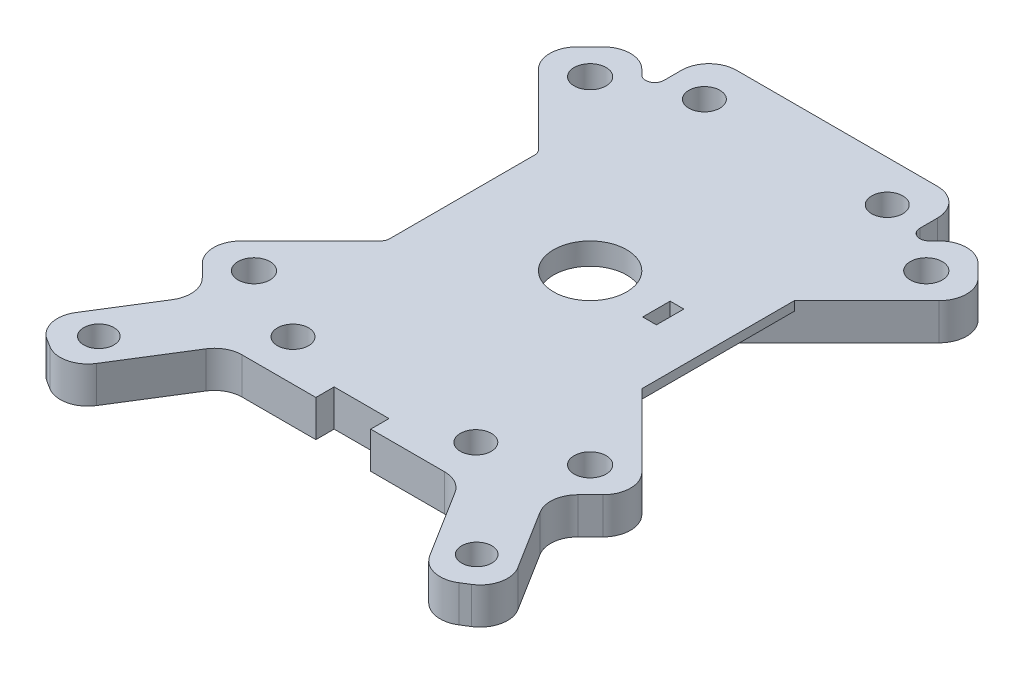
SolidWorks part; units mm, degrees
ref_plane "Front Plane" through (0, 0, 0) normal (0, 0, 1) x (1, 0, 0)
ref_plane "Top Plane" through (0, 0, 0) normal (0, 1, 0) x (1, 0, 0)
ref_plane "Right Plane" through (0, 0, 0) normal (1, 0, 0) x (0, 0, -1)
sketch "Sketch1" plane through (0, 0, 0) normal (0, 1, 0) x (1, 0, 0)
  line L1 (-14, -27) -> (14, -27)
  line L2 (-14, -27) -> (-14, 27)
  line L3 (-14, 27) -> (14, 27)
  line L4 (14, -27) -> (14, 27)
  line L5 (-14, -27) -> (14, 27) construction
  line L6 (-14, 27) -> (14, -27) construction
  point P0 (0, 0)
  dimension "D1" = 54
  dimension "D2" = 28
extrude "Boss-Extrude1" add sketch "Sketch1" along normal blind 4
sketch "Sketch10" plane through (0, 0, 0) normal (0, 1, 0) x (1, 0, 0)
  line L0 (-2.9682, -1.8547) -> (2.9682, 1.8547)
  line L1 (-2.9682, -1.8547) -> (19.8184, -38.3208)
  line L2 (2.9682, 1.8547) -> (25.7547, -34.6114)
  line L3 (19.8184, -38.3208) -> (25.7547, -34.6114)
  line L4 (0, -2.2) -> (0, 2.2) construction
  line L5 (-2.9682, 1.8547) -> (-25.7547, -34.6114)
  line L6 (-19.8184, -38.3208) -> (-25.7547, -34.6114)
  line L7 (2.9682, -1.8547) -> (-19.8184, -38.3208)
  line L8 (2.9682, -1.8547) -> (-2.9682, 1.8547)
  point P0 (0, 0)
  dimension "D1" = 32
  dimension "D2" = 43
  dimension "D3" = 7
extrude "Boss-Extrude4" add sketch "Sketch10" along normal blind 4 contours L8 L7 L1 L3 L2 L0 | L0 L8 L5 L6 L7 L1
sketch "Sketch2" plane through (0, 0, 0) normal (0, 1, 0) x (1, 0, 0)
  line L0 (2.8284, -2.8284) -> (24.0416, 18.3848)
  line L1 (2.8284, -2.8284) -> (-2.8284, 2.8284)
  line L2 (24.0416, 18.3848) -> (18.3848, 24.0416)
  line L3 (-2.8284, 2.8284) -> (18.3848, 24.0416)
  line L4 (14, 27) -> (-14, 27) construction
  line L10 (-2.8284, 2.8284) -> (2.8284, -2.8284)
  line L17 (-2.8284, -2.8284) -> (18.3848, -24.0416)
  line L18 (-2.8284, -2.8284) -> (2.8284, 2.8284)
  line L19 (2.8284, 2.8284) -> (24.0416, -18.3848)
  line L20 (18.3848, -24.0416) -> (24.0416, -18.3848)
  line L21 (-2.8284, 2.8284) -> (-24.0416, -18.3848)
  line L22 (-2.8284, 2.8284) -> (2.8284, -2.8284)
  line L23 (2.8284, -2.8284) -> (-18.3848, -24.0416)
  line L24 (-24.0416, -18.3848) -> (-18.3848, -24.0416)
  line L25 (2.8284, 2.8284) -> (-18.3848, 24.0416)
  line L26 (2.8284, 2.8284) -> (-2.8284, -2.8284)
  line L27 (-2.8284, -2.8284) -> (-24.0416, 18.3848)
  line L28 (-18.3848, 24.0416) -> (-24.0416, 18.3848)
  circle A1 centre (18.3848, 18.3848) radius 1.75
  circle A2 centre (18.3848, -18.3848) radius 1.75
  circle A3 centre (-18.3848, -18.3848) radius 1.75
  circle A4 centre (-18.3848, 18.3848) radius 1.75
  point P6 (0, 0)
  point P8 (0, 0)
  point P11 (0, 0)
  dimension "D4" = 3.5
  dimension "D1" = 135
  dimension "D2" = 8
  dimension "D3" = 30
  dimension "D5" = 4
extrude "Boss-Extrude2" add sketch "Sketch2" along normal blind 4
sketch "Sketch3" plane through (0, 4, 0) normal (0, 1, 0) x (1, 0, 0)
  circle A0 centre (10, -22.5) radius 1.7
  circle A1 centre (-10, -22.5) radius 1.7
  circle A2 centre (-10, 22.5) radius 1.7
  circle A3 centre (10, 22.5) radius 1.7
  dimension "D3" = 3.4
  dimension "D1" = 22.5
  dimension "D2" = 10
  dimension "D6" = 10
  dimension "D7" = 22.5
  dimension "D4" = 2
  dimension "D5" = 2
extrude "Cut-Extrude1" cut sketch "Sketch3" against normal blind 4
sketch "Sketch4" plane through (0, 4, 0) normal (0, 1, 0) x (1, 0, 0)
  line L1 (7.25, -1.5) -> (8.75, -1.5)
  line L2 (7.25, -1.5) -> (7.25, 1.5)
  line L3 (7.25, 1.5) -> (8.75, 1.5)
  line L4 (8.75, -1.5) -> (8.75, 1.5)
  line L5 (7.25, -1.5) -> (8.75, 1.5) construction
  line L6 (7.25, 1.5) -> (8.75, -1.5) construction
  circle A0 centre (0, 0) radius 4
  point P3 (8, 0)
  point P8 (8, 1.5)
  dimension "D1" = 8
  dimension "D2" = 8
  dimension "D3" = 1.5
  dimension "D4" = 3
extrude "Cut-Extrude2" cut sketch "Sketch4" against normal up to next
sketch "Sketch5" plane through (0, 0, 0) normal (0, -1, 0) x (1, 0, 0)
  line L0 (6.7082, -6) -> (-6.7082, -6)
  line L1 (6.7082, 6) -> (-6.7082, 6)
  arc A0 (6.7082, -6) -> (6.7082, 6) centre (0, 0) ccw
  arc A1 (-6.7082, 6) -> (-6.7082, -6) centre (0, 0) ccw
  dimension "D1" = 18
  dimension "D2" = 12
  dimension "D3" = 6
extrude "Cut-Extrude3" cut sketch "Sketch5" against normal blind 1.6
sketch "Sketch6" plane through (0, 0, 0) normal (0, -1, 0) x (1, 0, 0)
  line L0 (-10, -11) -> (-10, -17)
  line L1 (6, -11) -> (10, -11)
  line L2 (6, -11) -> (6, -17)
  line L3 (6, -17) -> (10, -17)
  line L4 (10, -11) -> (10, -17)
  line L5 (6, -11) -> (10, -17) construction
  line L6 (6, -17) -> (10, -11) construction
  line L7 (-10, -11) -> (-6, -11)
  line L8 (-6, -11) -> (-6, -17)
  line L9 (-10, -17) -> (-6, -17)
  line L10 (-10, 17) -> (-10, 11)
  line L11 (-10, 17) -> (-6, 17)
  line L12 (-6, 17) -> (-6, 11)
  line L13 (-10, 11) -> (-6, 11)
  line L14 (6, 17) -> (6, 11)
  line L15 (6, 17) -> (10, 17)
  line L16 (10, 17) -> (10, 11)
  line L17 (6, 11) -> (10, 11)
  point P0 (8, -14)
  point P5 (-8, -11)
  point P7 (-8, 11)
  point P8 (-6, 14)
  point P21 (6, 14)
  point P22 (-8, 17)
  point P23 (-10, 14)
  point P24 (8, 11)
  point P25 (8, -11)
  dimension "D5" = 2
  dimension "D1" = 8
  dimension "D2" = 14
  dimension "D3" = 4
  dimension "D4" = 6
  dimension "D7" = 8
  dimension "D8" = 14
  dimension "D6" = 2
extrude "Boss-Extrude3" [suppressed] add sketch "Sketch6" along normal blind 4
chamfer "Chamfer1" distance 3 angle 45 1 edges at (14, 0, 0)
fillet "Fillet1" radius 3 16 edges at (-14, 2, -27) (-18.3848, 2, -24.0416) (-24.0416, 2, -18.3848) (-24.0416, 2, 18.3848) (24.0416, 2, 18.3848) (24.0416, 2, -18.3848) (18.3848, 2, -24.0416) (14, 2, -27) (-18.8557, 2, 23.5707) (-12.7443, 2, 27) (12.7443, 2, 27) (18.8557, 2, 23.5707) (25.7547, 2, 34.6114) (19.8184, 2, 38.3208) (-19.8184, 2, 38.3208) (-25.7547, 2, 34.6114)
fillet "Fillet2" radius 1 4 edges at (14, 2, -19.6569) (-14, 2, 8.3431) (-14, 2, -8.3431) (-14, 2, -19.6569)
sketch "Sketch7" plane through (0, 0, 27) normal (0, 0, 1) x (1, 0, 0)
  line L0 (-11.0814, 4) -> (11.0814, 4) construction
  line L1 (-3, 4) -> (3, 4)
  line L2 (-3, 4) -> (-3, 0)
  line L3 (-3, 0) -> (3, 0)
  line L4 (3, 4) -> (3, 0)
  line L5 (-11.0814, 0) -> (11.0814, 0) construction
  point P8 (0, 0)
  point P9 (0, 4)
  dimension "D1" = 6
extrude "Cut-Extrude4" cut sketch "Sketch7" against normal blind 2
sketch "Sketch8" plane through (0, 0, 0) normal (0, 1, 0) x (-1, 0, 0)
  line L1 (-5, -27) -> (5, -27)
  line L2 (-5, -27) -> (-6.5, -6)
  line L3 (-6.5, -6) -> (6.5, -6)
  line L4 (5, -27) -> (6.5, -6)
  line L6 (6.7082, -6) -> (-6.7082, -6) construction
  line L7 (-11, -27) -> (11, -27) construction
  point P6 (0, -6)
  point P8 (0, -6)
  point P12 (0, -27)
  dimension "D1" = 13
  dimension "D2" = 10
extrude "Cut-Extrude5" cut sketch "Sketch8" along normal blind 1
sketch "Sketch9" plane through (0, 4, 0) normal (0, 1, 0) x (1, 0, 0)
  line L1 (0, 0) -> (20.6669, -33.0739) construction
  line L2 (0, -2.2) -> (0, 2.2) construction
  circle A0 centre (20.6669, -33.0739) radius 1.65
  circle A2 centre (-20.6669, -33.0739) radius 1.65
  point P2 (0, 0)
  point P3 (22.8796, -37.316)
  point P4 (-20.8685, -42.5719)
  dimension "D1" = 3.3
  dimension "D2" = 39
  dimension "D3" = 32
extrude "Cut-Extrude6" cut sketch "Sketch9" against normal up to next
equation "\"D6@Sketch3\"=\"D2@Sketch3\""
equation "\"D7@Sketch3\"=\"D1@Sketch3\""
equation "\"D3@Sketch5\"=\"D2@Sketch5\"/2"
equation "\"D7@Sketch6\"=\"D1@Sketch6\""
equation "\"D8@Sketch6\"=\"D2@Sketch6\""
